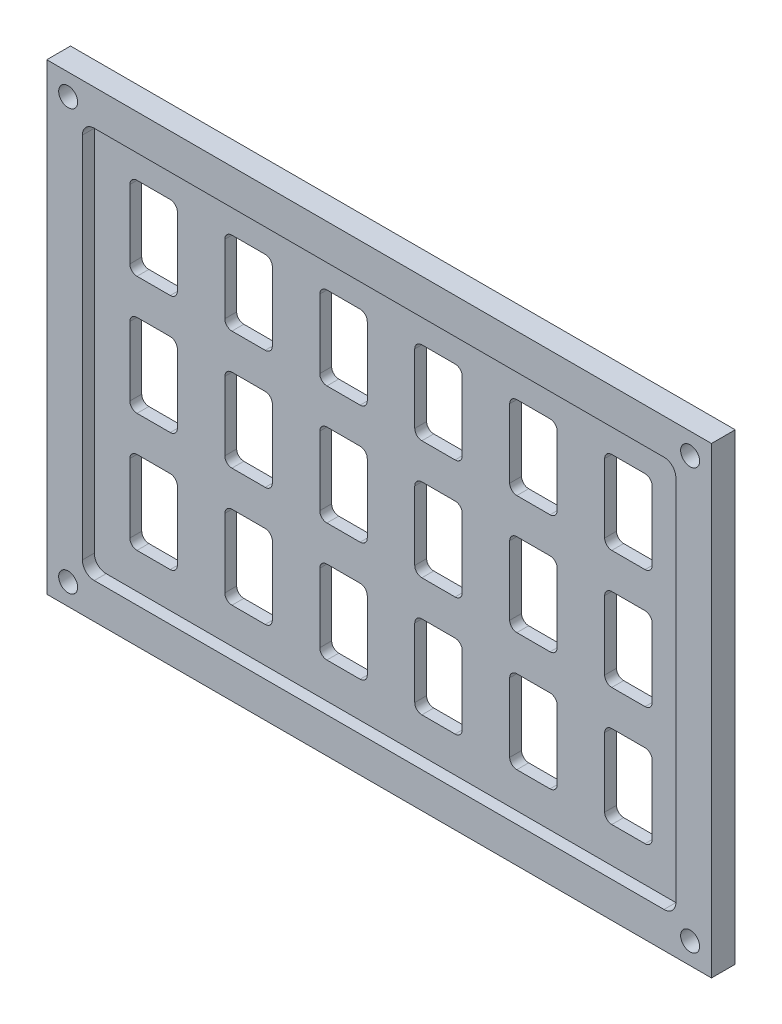
SolidWorks part; units mm, degrees
ref_plane "Front Plane" through (0, 0, 0) normal (0, 0, 1) x (1, 0, 0)
ref_plane "Top Plane" through (0, 0, 0) normal (0, 1, 0) x (1, 0, 0)
ref_plane "Right Plane" through (0, 0, 0) normal (1, 0, 0) x (0, 0, -1)
sketch "Sketch1" plane through (0, 0, 0) normal (0, 0, 1) x (1, 0, 0)
  line L0 (-70, 64.5) -> (-70, 35.5)
  line L1 (-140, -97.5) -> (140, -97.5)
  line L2 (-140, -97.5) -> (-140, 97.5)
  line L3 (-140, 97.5) -> (140, 97.5)
  line L4 (140, -97.5) -> (140, 97.5)
  line L5 (-140, -97.5) -> (140, 97.5) construction
  line L6 (-140, 97.5) -> (140, -97.5) construction
  line L7 (-107, 67.5) -> (-93, 67.5)
  line L8 (-110, 64.5) -> (-110, 35.5)
  line L9 (-107, 32.5) -> (-93, 32.5)
  line L10 (-90, 64.5) -> (-90, 35.5)
  line L11 (-110, 67.5) -> (-90, 32.5) construction
  line L12 (-110, 32.5) -> (-90, 67.5) construction
  line L13 (-67, 67.5) -> (-53, 67.5)
  line L14 (-50, 64.5) -> (-50, 35.5)
  line L15 (-67, 32.5) -> (-53, 32.5)
  line L16 (-30, 64.5) -> (-30, 35.5)
  line L17 (-27, 67.5) -> (-13, 67.5)
  line L18 (-10, 64.5) -> (-10, 35.5)
  line L19 (-27, 32.5) -> (-13, 32.5)
  line L20 (10, 64.5) -> (10, 35.5)
  line L21 (13, 67.5) -> (27, 67.5)
  line L22 (30, 64.5) -> (30, 35.5)
  line L23 (13, 32.5) -> (27, 32.5)
  line L24 (50, 64.5) -> (50, 35.5)
  line L25 (53, 67.5) -> (67, 67.5)
  line L26 (70, 64.5) -> (70, 35.5)
  line L27 (53, 32.5) -> (67, 32.5)
  line L28 (90, 64.5) -> (90, 35.5)
  line L29 (93, 67.5) -> (107, 67.5)
  line L30 (110, 64.5) -> (110, 35.5)
  line L31 (93, 32.5) -> (107, 32.5)
  line L32 (-70, 14.5) -> (-70, -14.5)
  line L33 (-67, 17.5) -> (-53, 17.5)
  line L34 (-50, 14.5) -> (-50, -14.5)
  line L35 (-67, -17.5) -> (-53, -17.5)
  line L36 (-30, 14.5) -> (-30, -14.5)
  line L37 (-27, 17.5) -> (-13, 17.5)
  line L38 (-10, 14.5) -> (-10, -14.5)
  line L39 (-27, -17.5) -> (-13, -17.5)
  line L40 (10, 14.5) -> (10, -14.5)
  line L41 (13, 17.5) -> (27, 17.5)
  line L42 (30, 14.5) -> (30, -14.5)
  line L43 (13, -17.5) -> (27, -17.5)
  line L44 (50, 14.5) -> (50, -14.5)
  line L45 (53, 17.5) -> (67, 17.5)
  line L46 (70, 14.5) -> (70, -14.5)
  line L47 (53, -17.5) -> (67, -17.5)
  line L48 (90, 14.5) -> (90, -14.5)
  line L49 (93, 17.5) -> (107, 17.5)
  line L50 (110, 14.5) -> (110, -14.5)
  line L51 (93, -17.5) -> (107, -17.5)
  line L52 (-70, -35.5) -> (-70, -64.5)
  line L53 (-67, -32.5) -> (-53, -32.5)
  line L54 (-50, -35.5) -> (-50, -64.5)
  line L55 (-67, -67.5) -> (-53, -67.5)
  line L56 (-30, -35.5) -> (-30, -64.5)
  line L57 (-27, -32.5) -> (-13, -32.5)
  line L58 (-10, -35.5) -> (-10, -64.5)
  line L59 (-27, -67.5) -> (-13, -67.5)
  line L60 (10, -35.5) -> (10, -64.5)
  line L61 (13, -32.5) -> (27, -32.5)
  line L62 (30, -35.5) -> (30, -64.5)
  line L63 (13, -67.5) -> (27, -67.5)
  line L64 (50, -35.5) -> (50, -64.5)
  line L65 (53, -32.5) -> (67, -32.5)
  line L66 (70, -35.5) -> (70, -64.5)
  line L67 (53, -67.5) -> (67, -67.5)
  line L68 (90, -35.5) -> (90, -64.5)
  line L69 (93, -32.5) -> (107, -32.5)
  line L70 (110, -35.5) -> (110, -64.5)
  line L71 (93, -67.5) -> (107, -67.5)
  line L72 (-110, 14.5) -> (-110, -14.5)
  line L73 (-107, 17.5) -> (-93, 17.5)
  line L74 (-90, 14.5) -> (-90, -14.5)
  line L75 (-107, -17.5) -> (-93, -17.5)
  line L76 (-110, -35.5) -> (-110, -64.5)
  line L77 (-107, -32.5) -> (-93, -32.5)
  line L78 (-90, -35.5) -> (-90, -64.5)
  line L79 (-107, -67.5) -> (-93, -67.5)
  line L80 (-110, 64.5) -> (-70, 64.5) construction
  line L81 (-110, 64.5) -> (-110, 14.5) construction
  arc A0 (-110, 35.5) -> (-107, 32.5) centre (-107, 35.5) ccw
  arc A1 (-93, 32.5) -> (-90, 35.5) centre (-93, 35.5) ccw
  arc A2 (-93, 67.5) -> (-90, 64.5) centre (-93, 64.5) cw
  arc A3 (-107, 67.5) -> (-110, 64.5) centre (-107, 64.5) ccw
  arc A4 (-67, 67.5) -> (-70, 64.5) centre (-67, 64.5) ccw
  arc A5 (-70, 35.5) -> (-67, 32.5) centre (-67, 35.5) ccw
  arc A6 (-53, 67.5) -> (-50, 64.5) centre (-53, 64.5) cw
  arc A7 (-53, 32.5) -> (-50, 35.5) centre (-53, 35.5) ccw
  arc A8 (-27, 67.5) -> (-30, 64.5) centre (-27, 64.5) ccw
  arc A9 (-30, 35.5) -> (-27, 32.5) centre (-27, 35.5) ccw
  arc A10 (-13, 67.5) -> (-10, 64.5) centre (-13, 64.5) cw
  arc A11 (-13, 32.5) -> (-10, 35.5) centre (-13, 35.5) ccw
  arc A12 (13, 67.5) -> (10, 64.5) centre (13, 64.5) ccw
  arc A13 (10, 35.5) -> (13, 32.5) centre (13, 35.5) ccw
  arc A14 (27, 67.5) -> (30, 64.5) centre (27, 64.5) cw
  arc A15 (27, 32.5) -> (30, 35.5) centre (27, 35.5) ccw
  arc A16 (53, 67.5) -> (50, 64.5) centre (53, 64.5) ccw
  arc A17 (50, 35.5) -> (53, 32.5) centre (53, 35.5) ccw
  arc A18 (67, 67.5) -> (70, 64.5) centre (67, 64.5) cw
  arc A19 (67, 32.5) -> (70, 35.5) centre (67, 35.5) ccw
  arc A20 (93, 67.5) -> (90, 64.5) centre (93, 64.5) ccw
  arc A21 (90, 35.5) -> (93, 32.5) centre (93, 35.5) ccw
  arc A22 (107, 67.5) -> (110, 64.5) centre (107, 64.5) cw
  arc A23 (107, 32.5) -> (110, 35.5) centre (107, 35.5) ccw
  arc A24 (-67, 17.5) -> (-70, 14.5) centre (-67, 14.5) ccw
  arc A25 (-70, -14.5) -> (-67, -17.5) centre (-67, -14.5) ccw
  arc A26 (-53, 17.5) -> (-50, 14.5) centre (-53, 14.5) cw
  arc A27 (-53, -17.5) -> (-50, -14.5) centre (-53, -14.5) ccw
  arc A28 (-27, 17.5) -> (-30, 14.5) centre (-27, 14.5) ccw
  arc A29 (-30, -14.5) -> (-27, -17.5) centre (-27, -14.5) ccw
  arc A30 (-13, 17.5) -> (-10, 14.5) centre (-13, 14.5) cw
  arc A31 (-13, -17.5) -> (-10, -14.5) centre (-13, -14.5) ccw
  arc A32 (13, 17.5) -> (10, 14.5) centre (13, 14.5) ccw
  arc A33 (10, -14.5) -> (13, -17.5) centre (13, -14.5) ccw
  arc A34 (27, 17.5) -> (30, 14.5) centre (27, 14.5) cw
  arc A35 (27, -17.5) -> (30, -14.5) centre (27, -14.5) ccw
  arc A36 (53, 17.5) -> (50, 14.5) centre (53, 14.5) ccw
  arc A37 (50, -14.5) -> (53, -17.5) centre (53, -14.5) ccw
  arc A38 (67, 17.5) -> (70, 14.5) centre (67, 14.5) cw
  arc A39 (67, -17.5) -> (70, -14.5) centre (67, -14.5) ccw
  arc A40 (93, 17.5) -> (90, 14.5) centre (93, 14.5) ccw
  arc A41 (90, -14.5) -> (93, -17.5) centre (93, -14.5) ccw
  arc A42 (107, 17.5) -> (110, 14.5) centre (107, 14.5) cw
  arc A43 (107, -17.5) -> (110, -14.5) centre (107, -14.5) ccw
  arc A44 (-67, -32.5) -> (-70, -35.5) centre (-67, -35.5) ccw
  arc A45 (-70, -64.5) -> (-67, -67.5) centre (-67, -64.5) ccw
  arc A46 (-53, -32.5) -> (-50, -35.5) centre (-53, -35.5) cw
  arc A47 (-53, -67.5) -> (-50, -64.5) centre (-53, -64.5) ccw
  arc A48 (-27, -32.5) -> (-30, -35.5) centre (-27, -35.5) ccw
  arc A49 (-30, -64.5) -> (-27, -67.5) centre (-27, -64.5) ccw
  arc A50 (-13, -32.5) -> (-10, -35.5) centre (-13, -35.5) cw
  arc A51 (-13, -67.5) -> (-10, -64.5) centre (-13, -64.5) ccw
  arc A52 (13, -32.5) -> (10, -35.5) centre (13, -35.5) ccw
  arc A53 (10, -64.5) -> (13, -67.5) centre (13, -64.5) ccw
  arc A54 (27, -32.5) -> (30, -35.5) centre (27, -35.5) cw
  arc A55 (27, -67.5) -> (30, -64.5) centre (27, -64.5) ccw
  arc A56 (53, -32.5) -> (50, -35.5) centre (53, -35.5) ccw
  arc A57 (50, -64.5) -> (53, -67.5) centre (53, -64.5) ccw
  arc A58 (67, -32.5) -> (70, -35.5) centre (67, -35.5) cw
  arc A59 (67, -67.5) -> (70, -64.5) centre (67, -64.5) ccw
  arc A60 (93, -32.5) -> (90, -35.5) centre (93, -35.5) ccw
  arc A61 (90, -64.5) -> (93, -67.5) centre (93, -64.5) ccw
  arc A62 (107, -32.5) -> (110, -35.5) centre (107, -35.5) cw
  arc A63 (107, -67.5) -> (110, -64.5) centre (107, -64.5) ccw
  arc A64 (-107, 17.5) -> (-110, 14.5) centre (-107, 14.5) ccw
  arc A65 (-110, -14.5) -> (-107, -17.5) centre (-107, -14.5) ccw
  arc A66 (-93, 17.5) -> (-90, 14.5) centre (-93, 14.5) cw
  arc A67 (-93, -17.5) -> (-90, -14.5) centre (-93, -14.5) ccw
  arc A68 (-107, -32.5) -> (-110, -35.5) centre (-107, -35.5) ccw
  arc A69 (-110, -64.5) -> (-107, -67.5) centre (-107, -64.5) ccw
  arc A70 (-93, -32.5) -> (-90, -35.5) centre (-93, -35.5) cw
  arc A71 (-93, -67.5) -> (-90, -64.5) centre (-93, -64.5) ccw
  point P0 (0, 0)
  point P6 (-100, 50)
  dimension "D7" = 3
  dimension "D1" = 280
  dimension "D2" = 195
  dimension "D3" = 35
  dimension "D4" = 20
  dimension "D5" = 30
  dimension "D6" = 30
  dimension "D10" = 90
  dimension "D11" = 40
  dimension "D12" = 50
  dimension "D8" = 6
  dimension "D9" = 3
extrude "Boss-Extrude1" add sketch "Sketch1" along normal blind 5
sketch "Sketch9" plane through (0, 0, 5) normal (0, 0, 1) x (1, 0, 0)
  line L0 (-125, 77.5) -> (-125, -77.5)
  line L1 (-120, -82.5) -> (120, -82.5)
  line L2 (125, -77.5) -> (125, 77.5)
  line L3 (120, 82.5) -> (-120, 82.5)
  line L4 (140, -97.5) -> (140, 97.5)
  line L5 (140, 97.5) -> (-140, 97.5)
  line L6 (-140, 97.5) -> (-140, -97.5)
  line L7 (-140, -97.5) -> (140, -97.5)
  line L8 (140, -97.5) -> (140, 97.5)
  line L9 (140, 97.5) -> (-140, 97.5)
  line L10 (-140, 97.5) -> (-140, -97.5)
  line L11 (-140, -97.5) -> (140, -97.5)
  line L12 (-125, 82.5) -> (-125, -82.5) construction
  line L13 (-125, -82.5) -> (125, -82.5) construction
  line L14 (125, -82.5) -> (125, 82.5) construction
  line L15 (125, 82.5) -> (-125, 82.5) construction
  arc A0 (-125, -77.5) -> (-120, -82.5) centre (-120, -77.5) ccw
  arc A1 (120, -82.5) -> (125, -77.5) centre (120, -77.5) ccw
  arc A2 (125, 77.5) -> (120, 82.5) centre (120, 77.5) ccw
  arc A3 (-125, 77.5) -> (-120, 82.5) centre (-120, 77.5) cw
  dimension "D3" = 5
  dimension "D1" = 0
  dimension "D2" = 15
extrude "Boss-Extrude2" add sketch "Sketch9" along normal blind 5
sketch "Sketch10" plane through (0, 0, 10) normal (0, 0, 1) x (1, 0, 0)
  line L0 (0, 0) -> (0, 67.2189) construction
  line L1 (0, -5.5) -> (0, 5.5) construction
  line L2 (0, 0) -> (84.4218, 0) construction
  line L3 (5.5, 0) -> (-5.5, 0) construction
  line L4 (-140, 97.5) -> (-140, -97.5) construction
  line L5 (140, 97.5) -> (-140, 97.5) construction
  circle A0 centre (-131, 88.5) radius 4
  circle A1 centre (131, 88.5) radius 4
  circle A2 centre (131, -88.5) radius 4
  circle A3 centre (-131, -88.5) radius 4
  point P12 (0, 0)
  point P14 (0, 0)
  dimension "D1" = 8
  dimension "D2" = 9
  dimension "D3" = 9
extrude "Cut-Extrude1" cut sketch "Sketch10" against normal through all
